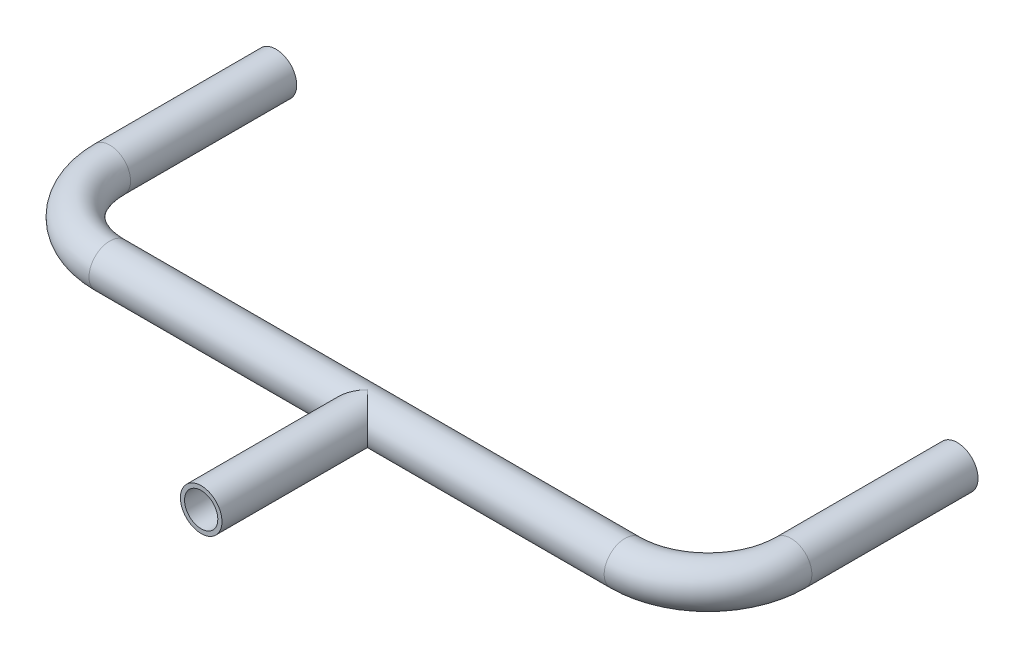
SolidWorks part; units mm, degrees
material "Copper"
ref_plane "Front Plane" through (0, 0, 0) normal (0, 0, 1) x (1, 0, 0)
ref_plane "Top Plane" through (0, 0, 0) normal (0, 1, 0) x (1, 0, 0)
ref_plane "Right Plane" through (0, 0, 0) normal (1, 0, 0) x (0, 0, -1)
sketch "Sketch2" plane through (0, 0, 0) normal (0, 1, 0) x (1, 0, 0)
  line L0 (0, 0) -> (-23597.9859, 0) construction
  line L1 (0, 0) -> (0, 23597.9859) construction
  line L2 (-41, 0) -> (-41, -20)
  line L3 (-31, -30) -> (31, -30)
  line L5 (41, -20) -> (41, 0)
  arc A0 (-41, -20) -> (-31, -30) centre (-31, -20) ccw
  arc A1 (41, -20) -> (31, -30) centre (31, -20) cw
  point P14 (0, -30)
  dimension "D3" = 10
  dimension "D1" = 82
  dimension "D2" = 30
  dimension "41" = 41
sketch "Sketch3" plane through (0, 0, 0) normal (0, 0, 1) x (1, 0, 0)
  line L0 (-31, 0) -> (-41, 0) construction
  line L1 (200000, 0) -> (-223597.9859, 0) construction
  circle A0 centre (-41, 0) radius 2
  circle A1 centre (-41, 0) radius 2.5
  dimension "D1" = 4
  dimension "D2" = 5
sweep "Sweep1" add profiles "Sketch3" path "Sketch2"
ref_plane "Plane1" through (0, 0, 30) normal (0, 0, 1) x (1, 0, 0)
sketch "Sketch5" plane through (0, 0, 30) normal (0, 0, 1) x (1, 0, 0)
  circle A0 centre (0, 0) radius 2.5
  circle A1 centre (0, 0) radius 2
  dimension "D1" = 5
  dimension "D2" = 4
extrude "Boss-Extrude2" add sketch "Sketch5" along normal blind 20
